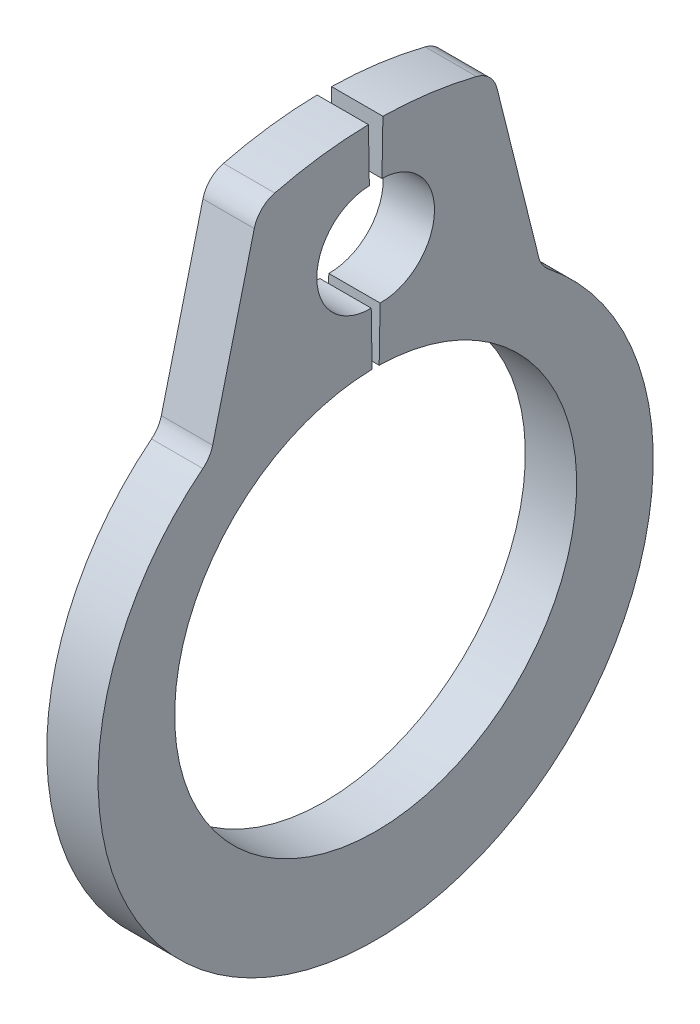
SolidWorks part; units mm, degrees
material "Cast Carbon Steel"
ref_plane "Front" through (0, 0, 0) normal (0, 0, 1) x (1, 0, 0)
ref_plane "Top" through (0, 0, 0) normal (0, 1, 0) x (1, 0, 0)
ref_plane "Right" through (0, 0, 0) normal (1, 0, 0) x (0, 0, -1)
sketch "Sketch1" plane through (0, 0, 0) normal (1, 0, 0) x (0, 0, -1)
  line L0 (0, 0) -> (0, 2.35) construction
  line L1 (-0.041, 2.3496) -> (-0.0846, 4.8493) construction
  line L2 (-0.0846, 4.8493) -> (-1.3287, 4.8275) construction
  line L3 (-1.3287, 4.8275) -> (-1.9335, 2.4018) construction
  line L4 (0.0846, 4.8493) -> (0.041, 2.3496) construction
  line L5 (0.0846, 4.8493) -> (1.3287, 4.8275) construction
  line L6 (1.3287, 4.8275) -> (1.9335, 2.4018) construction
  line L7 (-1.9335, 2.4018) -> (-1.4736, 1.8306) construction
  line L8 (1.9335, 2.4018) -> (1.4736, 1.8306) construction
  line L9 (0, -2.35) -> (0, -3.45) construction
  line L10 (-1.3287, 4.8275) -> (-0.041, 2.3496) construction
  line L11 (0.041, 2.3496) -> (0.0519, 2.9745)
  line L12 (0, 2.35) -> (0, 4.85) construction
  line L13 (1.3725, 4.6518) -> (1.9335, 2.4018)
  line L14 (-1.3725, 4.6518) -> (-1.9335, 2.4018)
  line L16 (0.0737, 4.2244) -> (0.0846, 4.8493)
  line L17 (-0.0737, 4.2244) -> (-0.0846, 4.8493)
  line L18 (-0.0519, 2.9745) -> (-0.041, 2.3496)
  circle A0 centre (0, 0) radius 2.35 construction
  arc A1 (-0.041, 2.3496) -> (0.041, 2.3496) centre (0, 0) ccw
  circle A2 centre (0, -0.2047) radius 3.2453 construction
  arc A3 (0.0737, 4.2244) -> (0.0519, 2.9745) centre (0.0628, 3.5995) cw
  arc A4 (-0.0519, 2.9745) -> (-0.0737, 4.2244) centre (-0.0628, 3.5995) cw
  arc A6 (-1.9335, 2.4018) -> (1.9335, 2.4018) centre (0, -0.2047) ccw
  arc A7 (0.0846, 4.8493) -> (1.3725, 4.6518) centre (0, 0) cw
  arc A8 (-0.0846, 4.8493) -> (-1.3725, 4.6518) centre (0, 0) ccw
  dimension "A" = 4.7
  dimension "Smin" = 0.7333
  dimension "D1" = 75
  dimension "Angle" = 1
  dimension "H" = 2.5
  dimension "D2" = 1.25
extrude "Extrude1" add sketch "Sketch1" along normal mid plane 0.6
fillet "Fillet1" radius 0.33 4 edges at (0, 2.4018, 1.9335) (0, 4.6518, 1.3725) (0, 4.6518, -1.3725) (0, 2.4018, -1.9335)
sketch "Sketch2" plane through (0, 0, 0) normal (0, 0, 1) x (1, 0, 0)
  line L0 (-1.75, 0) -> (5.25, 0)
  line L1 (5.25, 0) -> (5.25, -2.5)
  line L2 (-0.35, -2.5) -> (-1.65, -2.5)
  line L3 (5.25, -2.5) -> (0.35, -2.5)
  line L4 (0.35, -2.5) -> (0.35, -2.4)
  line L5 (0.35, -2.4) -> (-0.35, -2.4)
  line L6 (-0.35, -2.4) -> (-0.35, -2.5)
  line L7 (-0.35, -2.5) -> (-1.75, -2.5) construction
  line L8 (-1.75, -2.5) -> (-1.75, 0) construction
  line L9 (0, -2.4) -> (0, 0) construction
  line L10 (5.25, 0) -> (14.0551, 0) construction
  line L11 (-1.65, -2.5) -> (-1.75, -2.4)
  line L12 (-1.75, -2.4) -> (-1.75, 0)
  dimension "D2" = 7
  dimension "D3" = 1.75
  dimension "D1" = 45
revolve "Revolve1" [suppressed] add sketch "Sketch2" angle 360 about L10
equation "\"D2@Sketch2\" = \"W@Sketch2\"*10"
equation "\"D3@Sketch2\" = \"D2@Sketch2\"/4"
equation "\"Smin@Sketch1\" = \"Smax@Sketch1\"/1.5"
equation "\"D2@Sketch1\" = \"H@Sketch1\"/2"
